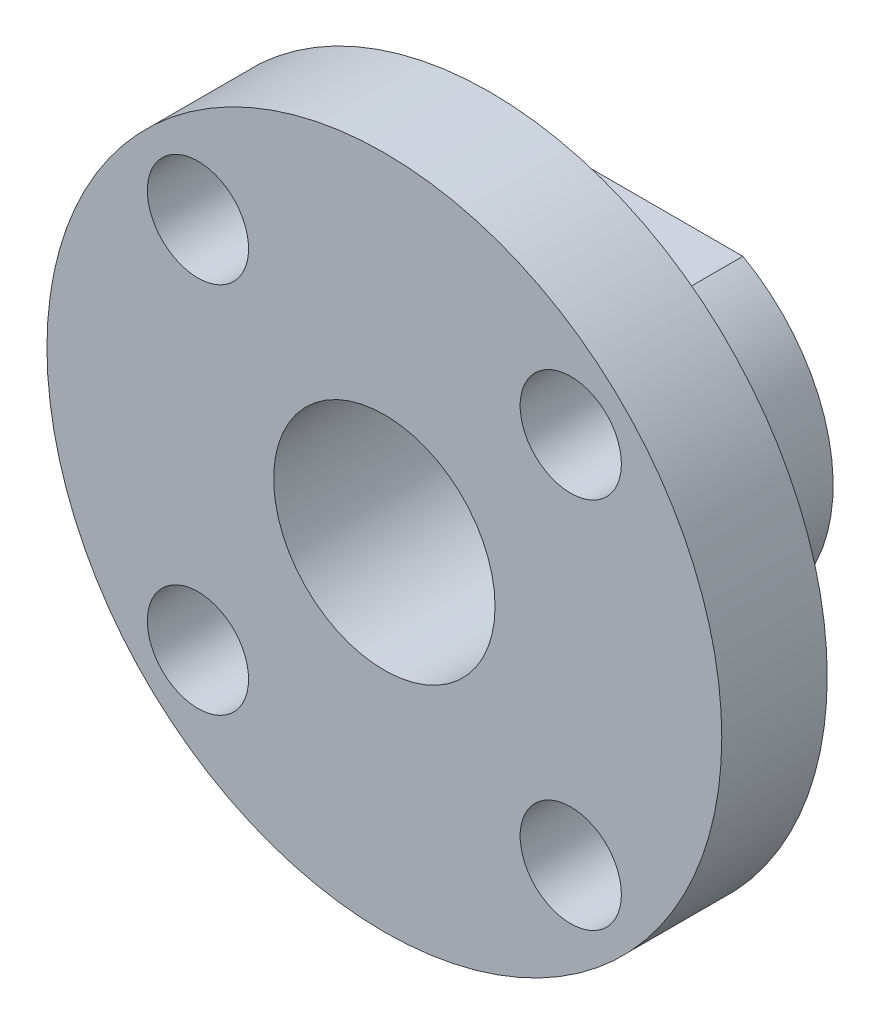
SolidWorks part; units mm, degrees
material "ABS"
ref_plane "Front Plane" through (0, 0, 0) normal (0, 0, 1) x (1, 0, 0)
ref_plane "Top Plane" through (0, 0, 0) normal (0, 1, 0) x (1, 0, 0)
ref_plane "Right Plane" through (0, 0, 0) normal (1, 0, 0) x (0, 0, -1)
sketch "Sketch12" plane through (0, 0, 0) normal (0, 0, 1) x (1, 0, 0)
  circle A0 centre (0, 0) radius 16
  dimension "D1" = 32
extrude "Boss-Extrude3" add sketch "Sketch12" along normal blind 5
sketch "Sketch14" plane through (0, 0, 0) normal (0, 0, 1) x (1, 0, 0)
  line L1 (8.8388, 8.8388) -> (-8.8388, 8.8388) construction
  line L2 (8.8388, 8.8388) -> (8.8388, -8.8388) construction
  line L3 (8.8388, -8.8388) -> (-8.8388, -8.8388) construction
  line L4 (-8.8388, 8.8388) -> (-8.8388, -8.8388) construction
  line L5 (8.8388, 8.8388) -> (-8.8388, -8.8388) construction
  line L6 (8.8388, -8.8388) -> (-8.8388, 8.8388) construction
  circle A0 centre (0, 0) radius 12.5 construction
  circle A1 centre (8.8388, 8.8388) radius 2.4
  circle A2 centre (-8.8388, 8.8388) radius 2.4
  circle A3 centre (8.8388, -8.8388) radius 2.4
  circle A4 centre (-8.8388, -8.8388) radius 2.4
  dimension "D1" = 25
  dimension "D2" = 4.8
extrude "Cut-Extrude3" cut sketch "Sketch14" along normal up to next
sketch "Sketch16" plane through (0, 0, 0) normal (0, 0, 1) x (1, 0, 0)
  line L0 (4, 7.25) -> (-4, 7.25)
  arc A0 (-4, 7.25) -> (4, 7.25) centre (0, 0) ccw
  arc A1 (4, 7.25) -> (-4, 7.25) centre (0, 0) ccw construction
  circle A2 centre (0, 0) radius 5.25 construction
  point P5 (0, 5.25)
  dimension "D1" = 2
  dimension "D3" = 10.5
  dimension "D2" = 8
extrude "Boss-Extrude4" add sketch "Sketch16" against normal blind 8
sketch "Sketch15" plane through (0, 0, 0) normal (0, 0, 1) x (1, 0, 0)
  circle A0 centre (0, 0) radius 5.25
  dimension "D1" = 10.5
extrude "Cut-Extrude4" cut sketch "Sketch15" against normal mid plane 20
sketch "Sketch17" plane through (0, 7.25, 0) normal (0, 1, 0) x (1, 0, 0)
  line L0 (4, 4) -> (-4, 4) construction
  line L1 (4, 8) -> (4, 0) construction
  line L2 (-4, 8) -> (-4, 0) construction
  circle A0 centre (0, 4) radius 2.4
  point P6 (0, 4)
  dimension "D1" = 4.8
extrude "Cut-Extrude5" cut sketch "Sketch17" against normal up to next
sketch "Sketch18" plane through (0, 0, -8) normal (0, 0, -1) x (-1, 0, 0)
  line L0 (-4, 7.25) -> (4, 7.25) construction
  line L1 (-4, 7.25) -> (4, 7.25) construction
  line L2 (0, 7.25) -> (0, 5.25) construction
  circle A0 centre (0, 0) radius 5.25 construction
  circle A1 centre (0, 0) radius 5.25 construction
  dimension "D1" = 2
